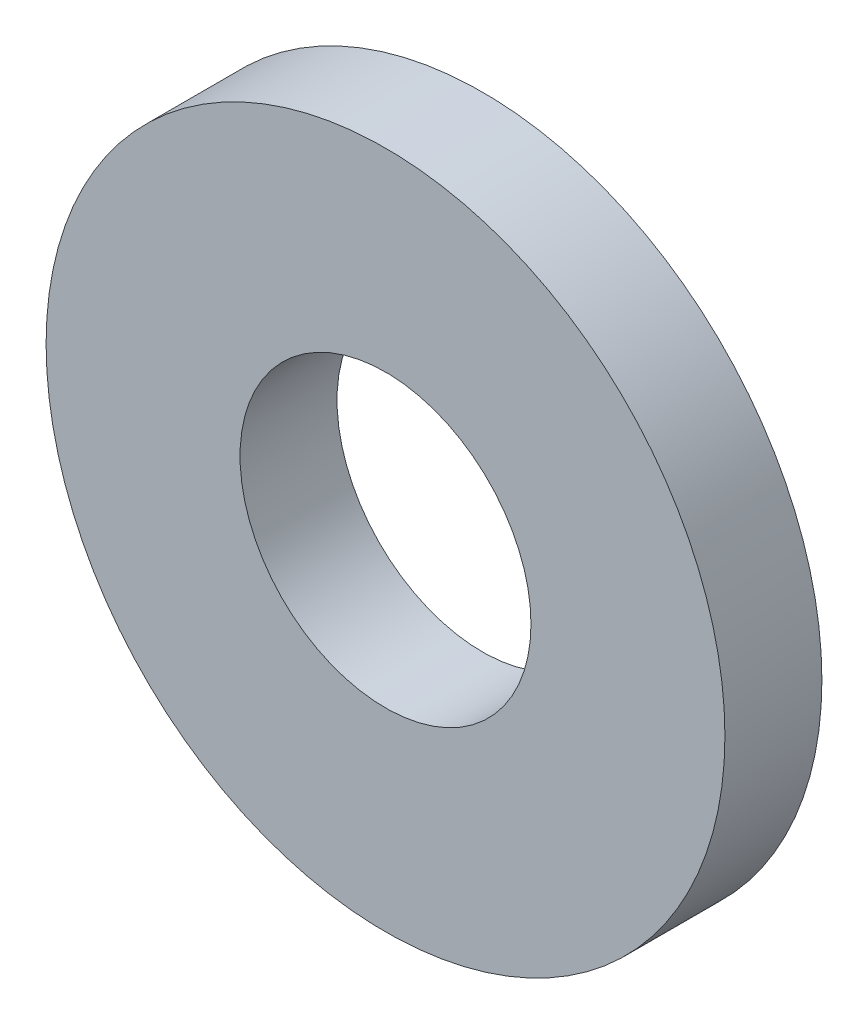
SolidWorks part; units mm, degrees
material "PTFE(普通)"
ref_plane "Front" through (0, 0, 0) normal (0, 0, 1) x (1, 0, 0)
ref_plane "Top" through (0, 0, 0) normal (0, 1, 0) x (1, 0, 0)
ref_plane "Right" through (0, 0, 0) normal (1, 0, 0) x (0, 0, -1)
sketch "草图1" plane through (0, 0, 0) normal (0, 0, 1) x (1, 0, 0)
  circle A0 centre (0, 0) radius 3
  circle A1 centre (0, 0) radius 7
  dimension "内径" = 6
  dimension "外径" = 14
extrude "凸台-拉伸1" add sketch "草图1" along normal mid plane 2
other "冻结***"
